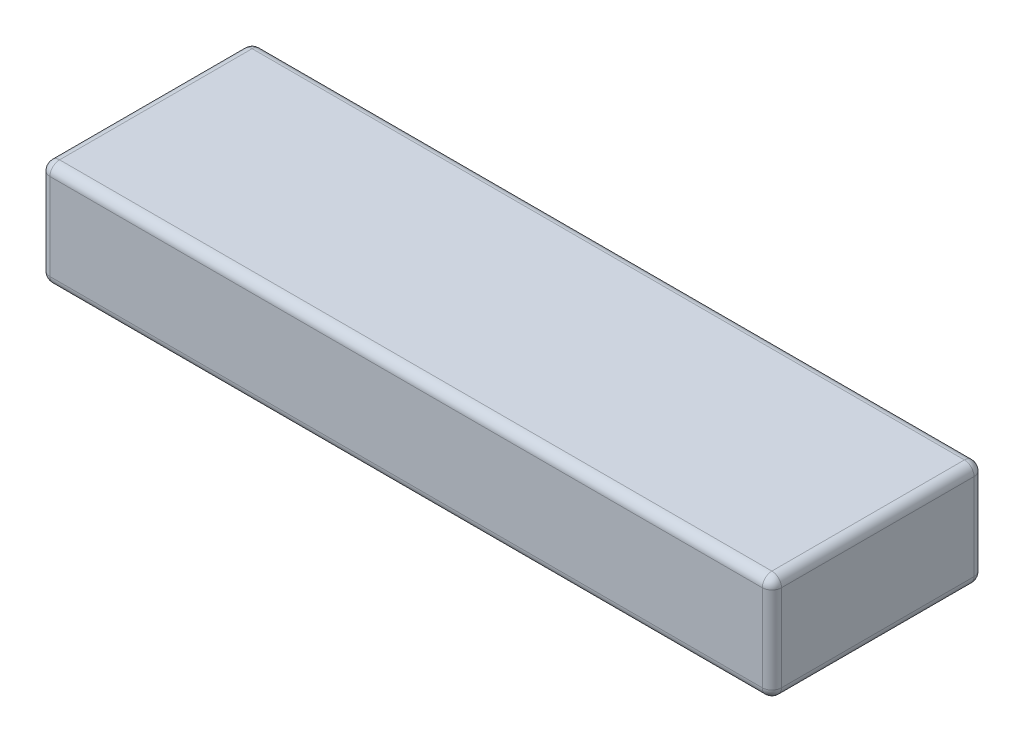
SolidWorks part; units mm, degrees
ref_plane "前视基准面" through (0, 0, 0) normal (0, 0, 1) x (1, 0, 0)
ref_plane "上视基准面" through (0, 0, 0) normal (0, 1, 0) x (1, 0, 0)
ref_plane "右视基准面" through (0, 0, 0) normal (1, 0, 0) x (0, 0, -1)
other "Configuration Table"
sketch "草图1" plane through (0, 0, 0) normal (0, 1, 0) x (1, 0, 0)
  line L1 (-76, -22) -> (76, -22)
  line L2 (-76, -22) -> (-76, 22)
  line L3 (-76, 22) -> (76, 22)
  line L4 (76, -22) -> (76, 22)
  line L5 (-76, -22) -> (76, 22) construction
  line L6 (-76, 22) -> (76, -22) construction
  point P0 (0, 0)
  dimension "D1" = 152
  dimension "D2" = 44
extrude "凸台-拉伸1" add sketch "草图1" along normal blind 22
fillet "圆角1" radius 2 12 edges at (76, 11, -22) (-76, 11, -22) (0, 0, -22) (-76, 0, 0) (76, 0, 0) (-76, 11, 22) (76, 11, 22) (0, 0, 22) (0, 22, 22) (-76, 22, 0) (0, 22, -22) (76, 22, 0)
